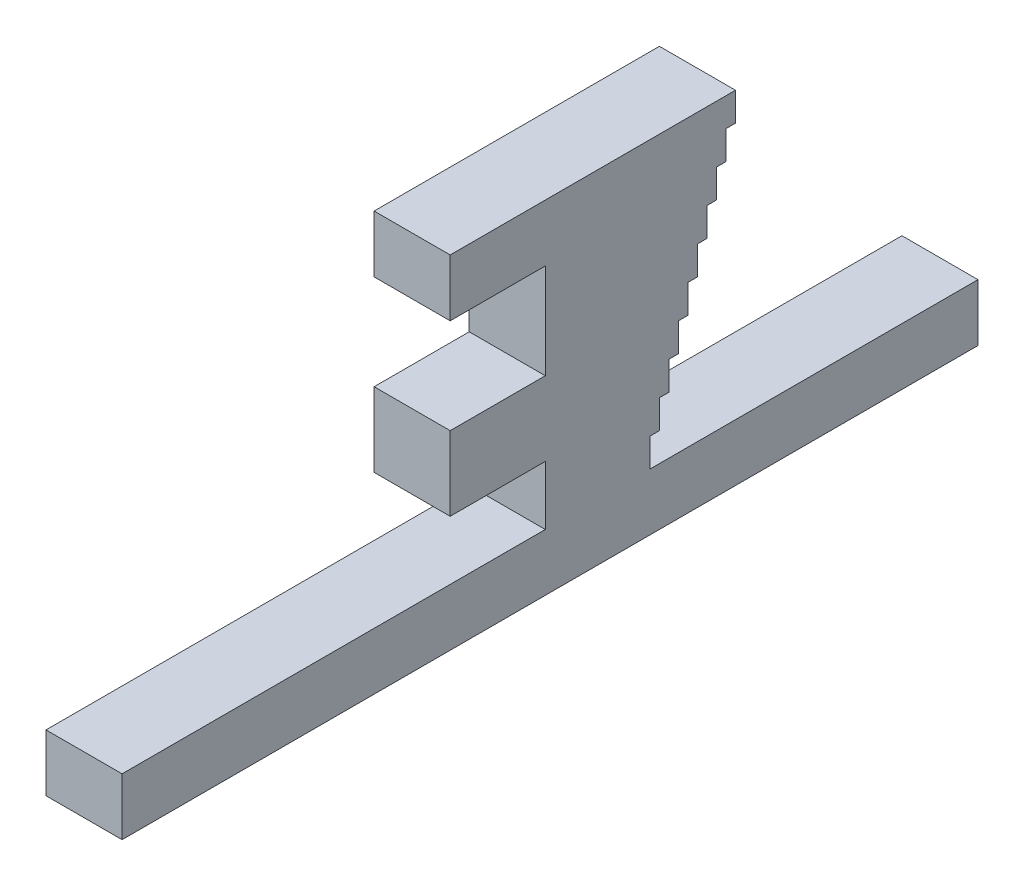
SolidWorks part; units mm, degrees
ref_plane "Front Plane" through (0, 0, 0) normal (0, 0, 1) x (1, 0, 0)
ref_plane "Top Plane" through (0, 0, 0) normal (0, 1, 0) x (1, 0, 0)
ref_plane "Right Plane" through (0, 0, 0) normal (1, 0, 0) x (0, 0, -1)
sketch "Sketch1" plane through (0, 0, 0) normal (1, 0, 0) x (0, 0, -1)
  line L0 (-4, 0) -> (13.25, 0)
  line L1 (13.25, 0) -> (13.25, -3)
  line L2 (13.25, -3) -> (-31.75, -3)
  line L3 (-31.75, -3) -> (-31.75, 0)
  line L4 (-31.75, 0) -> (-14.5, 0)
  line L29 (-14.5, 15) -> (0.5, 15)
  line L30 (0.5, 15) -> (0.5, 13.5)
  line L31 (0.5, 13.5) -> (0, 13.5)
  line L32 (0, 13.5) -> (0, 12)
  line L33 (0, 12) -> (-0.5, 12)
  line L34 (-0.5, 12) -> (-0.5, 10.5)
  line L35 (-0.5, 10.5) -> (-1, 10.5)
  line L36 (-1, 10.5) -> (-1, 9)
  line L37 (-1, 9) -> (-1.5, 9)
  line L38 (-1.5, 9) -> (-1.5, 7.5)
  line L39 (-1.5, 7.5) -> (-2, 7.5)
  line L40 (-2, 7.5) -> (-2, 6)
  line L41 (-2, 6) -> (-2.5, 6)
  line L42 (-2.5, 6) -> (-2.5, 4.5)
  line L43 (-2.5, 4.5) -> (-3, 4.5)
  line L44 (-3, 4.5) -> (-3, 3)
  line L45 (-3, 3) -> (-3.5, 3)
  line L46 (-3.5, 3) -> (-3.5, 1.5)
  line L47 (-3.5, 1.5) -> (-4, 1.5)
  line L48 (-4, 1.5) -> (-4, 0)
  line L51 (-14.5, 0) -> (-9.5, 0)
  line L54 (-9.5, 0) -> (-9.5, 3.1)
  line L56 (-9.5, 12) -> (-14.5, 12)
  line L58 (-14.5, 15) -> (-14.5, 12)
  line L59 (-9.5, 12) -> (-9.5, 7)
  line L60 (-9.5, 7) -> (-14.5, 7)
  line L61 (-14.5, 7) -> (-14.5, 3.1)
  line L62 (-9.5, 3.1) -> (-14.5, 3.1)
  point P28 (0, 0)
  dimension "D1" = 5
  dimension "D2" = 45
  dimension "D3" = 1.5
  dimension "D4" = 3
  dimension "D5" = 15
  dimension "D6" = 0.5
  dimension "D7" = 5
  dimension "D8" = 3.1
  dimension "D9" = 5
  dimension "D10" = 3
extrude "Boss-Extrude1" add sketch "Sketch1" along normal blind 4
